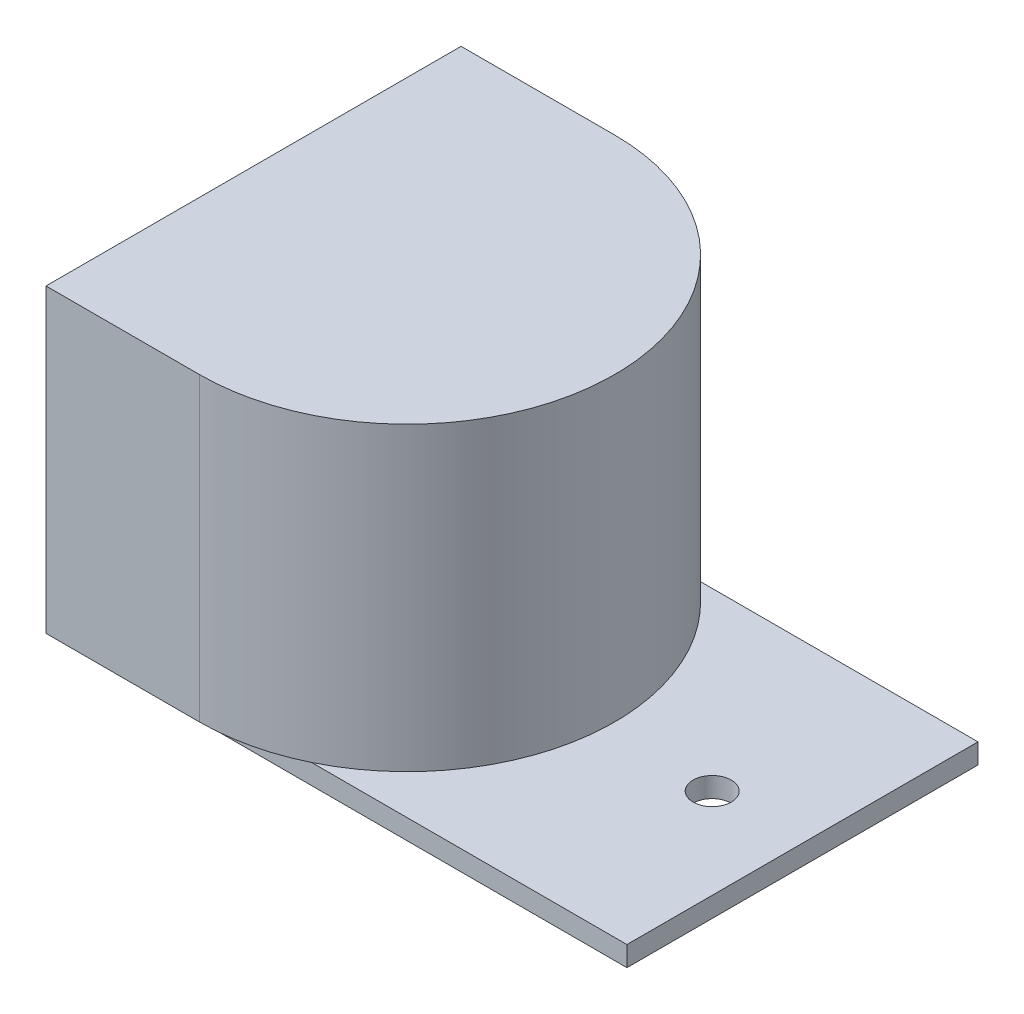
SolidWorks part; units mm, degrees
ref_plane "Front Plane" through (0, 0, 0) normal (0, 0, 1) x (1, 0, 0)
ref_plane "Top Plane" through (0, 0, 0) normal (0, 1, 0) x (1, 0, 0)
ref_plane "Right Plane" through (0, 0, 0) normal (1, 0, 0) x (0, 0, -1)
sketch "Sketch1" plane through (0, 0, 0) normal (0, 1, 0) x (1, 0, 0)
  line L1 (90, -175) -> (-420, -175)
  line L2 (90, -175) -> (90, 175)
  line L3 (90, 175) -> (-420, 175)
  line L4 (-420, -175) -> (-420, 175)
  line L5 (90, -175) -> (-420, 175) construction
  line L6 (90, 175) -> (-420, -175) construction
  circle A0 centre (0, 0) radius 19.05
  circle A1 centre (-347.89, 125.98) radius 12.5
  circle A2 centre (-352, -113.99) radius 12.5
  point P0 (-165, 0)
  dimension "D4" = 38.1
  dimension "D5" = 72.11
  dimension "D8" = 25
  dimension "D1" = 350
  dimension "D2" = 510
  dimension "D3" = 165
  dimension "D6" = 49.02
  dimension "D7" = 61.01
  dimension "D9" = 68
extrude "Boss-Extrude1" add sketch "Sketch1" along normal blind 20
sketch "Sketch2" plane through (0, 20, 0) normal (0, 1, 0) x (1, 0, 0)
  line L0 (-315.1367, -195.9778) -> (-468.2181, -195.9778)
  line L1 (-468.2181, -195.9778) -> (-468.2181, 217.8466)
  line L2 (-468.2181, 217.8466) -> (-315.1367, 217.8466)
  arc A0 (-315.1367, 217.8466) -> (-315.1367, -195.9778) centre (-315.1367, 10.9344) cw
surface "Surface-Extrude1" sketch "Sketch2" parameters "D1"=300
surface "Surface-Plane1"
sketch "Sketch3" plane through (0, 20, 0) normal (0, 1, 0) x (1, 0, 0)
  line L0 (-420, 175) -> (-420, -175) construction
  line L1 (90, 175) -> (-420, 175) construction
  line L2 (-420, -175) -> (90, -175) construction
  circle A0 centre (-295, 80) radius 9
  circle A1 centre (-295, -80) radius 9
  point P6 (0, 0)
  dimension "D1" = 125
  dimension "D4" = 18
  dimension "D2" = 95
  dimension "D3" = 95
extrude "Boss-Extrude2" add sketch "Sketch3" along normal blind 265
